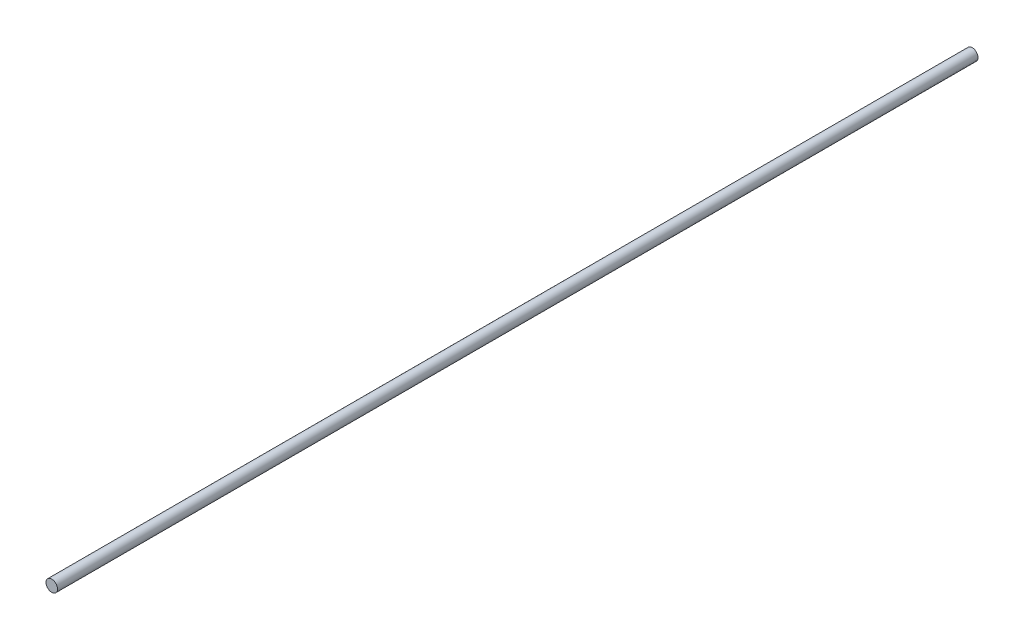
SolidWorks part; units mm, degrees
ref_plane "Front Plane" through (0, 0, 0) normal (0, 0, 1) x (1, 0, 0)
ref_plane "Top Plane" through (0, 0, 0) normal (0, 1, 0) x (1, 0, 0)
ref_plane "Right Plane" through (0, 0, 0) normal (1, 0, 0) x (0, 0, -1)
sketch "Sketch1" plane through (0, 0, 0) normal (0, 0, 1) x (1, 0, 0)
  circle A0 centre (0, 0) radius 3.75
  dimension "D1" = 7.5
extrude "Boss-Extrude1" add sketch "Sketch1" against normal blind 600
